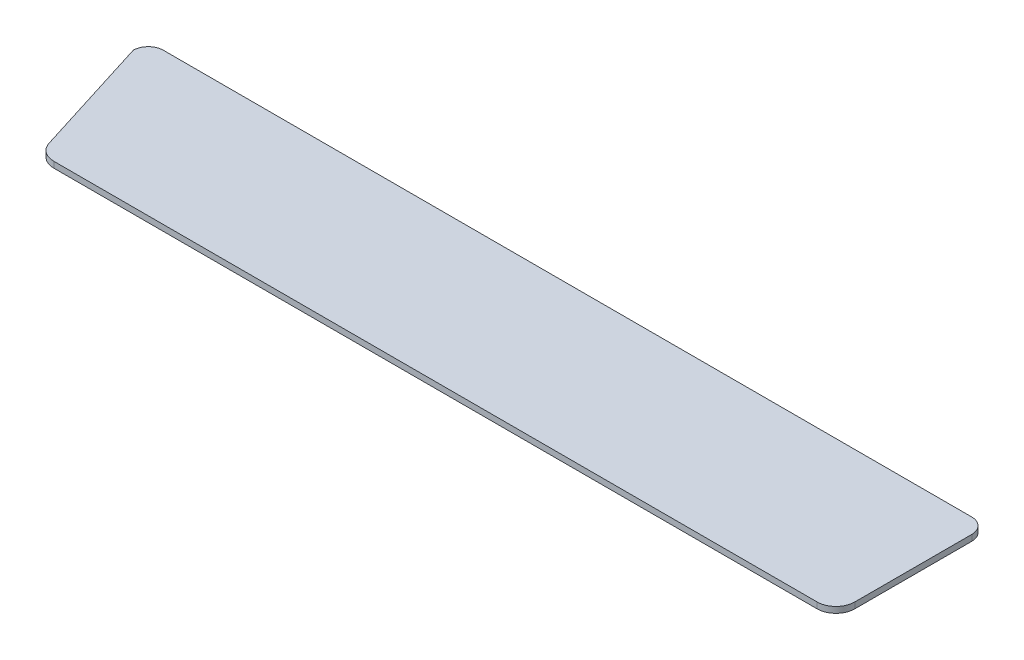
SolidWorks part; units mm, degrees
ref_plane "Front" through (0, 0, 0) normal (0, 0, 1) x (1, 0, 0)
ref_plane "Top" through (0, 0, 0) normal (0, 1, 0) x (1, 0, 0)
ref_plane "Right" through (0, 0, 0) normal (1, 0, 0) x (0, 0, -1)
sketch "Sketch1" plane through (0, 0, 0) normal (0, 1, 0) x (1, 0, 0)
  line L0 (0, 142) -> (42, 8)
  line L1 (0, 0) -> (444.5, 0)
  line L2 (0, 0) -> (0, 150)
  line L3 (0, 150) -> (444.5, 150)
  line L4 (444.5, 0) -> (444.5, 150)
  circle A0 centre (8, 142) radius 8
  circle A1 centre (50, 8) radius 8
  circle A2 centre (436.5, 142) radius 8
  circle A3 centre (436.5, 8) radius 8
  dimension "D3" = 8
  dimension "D5" = 8
  dimension "D7" = 8
  dimension "D9" = 8
  dimension "D1" = 150
  dimension "D2" = 444.5
  dimension "D4" = 8
  dimension "D6" = 50
  dimension "D8" = 8
  dimension "D10" = 8
extrude "Boss-Extrude1" add sketch "Sketch1" along normal blind 3.175 contours A3 L4 A2 L3 A0 L0 A1 L1 | A1 | A0 L0 | A2 | A3
sketch "Sketch2" plane through (0, 0, 0) normal (0, 0, 1) x (1, 0, 0)
  line L1 (-78.5546, 38.0306) -> (518.9117, 38.0306)
  line L2 (-78.5546, 38.0306) -> (-78.5546, -22.9419)
  line L3 (-78.5546, -22.9419) -> (518.9117, -22.9419)
  line L4 (518.9117, 38.0306) -> (518.9117, -22.9419)
extrude "Cut-Extrude1" cut sketch "Sketch2" against normal blind 70
fillet "Fillet1" radius 10 1 edges at (22.5672, 1.5875, -70)
fillet "Fillet2" radius 10 1 edges at (444.5, 1.5875, -70)
